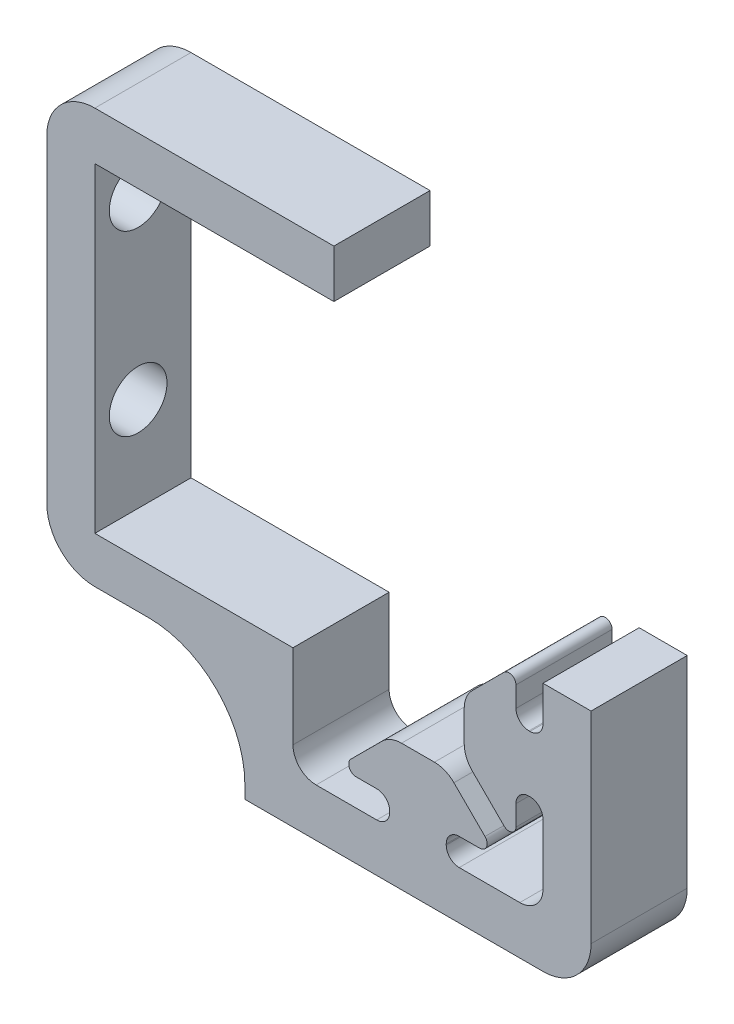
SolidWorks part; units mm, degrees
ref_plane "Front Plane" through (0, 0, 0) normal (0, 0, 1) x (1, 0, 0)
ref_plane "Top Plane" through (0, 0, 0) normal (0, 1, 0) x (1, 0, 0)
ref_plane "Right Plane" through (0, 0, 0) normal (1, 0, 0) x (0, 0, -1)
sketch "Sketch1" plane through (0, 0, 0) normal (0, 0, 1) x (1, 0, 0)
  line L0 (-10.5918, -13) -> (-4.3059, -13)
  line L1 (-4.3059, -13) -> (-4.2875, -13)
  line L2 (-2.9385, -11.651) -> (-2.9385, -11.5392)
  line L3 (-4.2875, -10.1902) -> (-6.4164, -10.1902)
  line L4 (-6.9677, -8.8575) -> (-3.7403, -5.636)
  line L5 (-1.7093, -4.7958) -> (1.7093, -4.7958)
  line L6 (3.7403, -5.636) -> (6.9677, -8.8575)
  line L7 (6.4164, -10.1902) -> (4.2875, -10.1902)
  line L8 (2.9385, -11.5392) -> (2.9385, -11.651)
  line L9 (4.2875, -13) -> (5.3216, -13)
  line L10 (5.3216, -13) -> (10.5918, -13)
  line L11 (13, -10.5918) -> (13, -5.3171)
  line L12 (13, -5.3171) -> (13, -4.2875)
  line L13 (11.651, -2.9385) -> (11.5392, -2.9385)
  line L14 (10.1902, -4.2875) -> (10.1902, -6.4021)
  line L15 (8.949, -6.917) -> (5.6529, -3.6284)
  line L16 (4.8085, -1.5932) -> (4.8085, 1.5932)
  line L17 (5.6529, 3.6284) -> (8.949, 6.917)
  line L18 (10.1902, 6.4021) -> (10.1902, 4.2875)
  line L19 (11.5392, 2.9385) -> (11.651, 2.9385)
  line L20 (13, 4.2875) -> (13, 5.3171)
  line L21 (13, 5.3171) -> (13, 10.5918) construction
  line L22 (10.5918, 13) -> (5.3216, 13) construction
  line L23 (5.3216, 13) -> (4.2875, 13) construction
  line L24 (2.9385, 11.651) -> (2.9385, 11.5392) construction
  line L25 (4.2875, 10.1902) -> (6.4768, 10.1902) construction
  line L26 (6.9951, 8.9367) -> (3.6864, 5.6355) construction
  line L27 (1.6558, 4.7958) -> (-1.6558, 4.7958) construction
  line L28 (-3.6864, 5.6355) -> (-6.9951, 8.9367) construction
  line L29 (-6.4768, 10.1902) -> (-4.2875, 10.1902) construction
  line L30 (-2.9385, 11.5392) -> (-2.9385, 11.651) construction
  line L31 (-4.2875, 13) -> (-4.3059, 13) construction
  line L32 (-4.3059, 13) -> (-10.5918, 13) construction
  line L33 (-13, 10.5918) -> (-13, 5.3171) construction
  line L34 (-13, 5.3171) -> (-13, 4.2875) construction
  line L35 (-11.651, 2.9385) -> (-11.5392, 2.9385) construction
  line L36 (-10.1902, 4.2875) -> (-10.1902, 6.4021) construction
  line L37 (-8.949, 6.917) -> (-5.6529, 3.6284) construction
  line L38 (-4.8085, 1.5932) -> (-4.8085, -1.5932) construction
  line L39 (-5.6529, -3.6284) -> (-8.949, -6.917) construction
  line L40 (-10.1902, -6.4021) -> (-10.1902, -4.2875) construction
  line L41 (-11.5392, -2.9385) -> (-11.651, -2.9385) construction
  line L42 (-13, -4.2875) -> (-13, -10.5918)
  line L44 (13, 5.3171) -> (13, 7.9544)
  line L45 (-33.4, 31.3527) -> (-13, 31.3527) construction
  line L46 (-33.4, 31.3527) -> (-33.4, -1.6473) construction
  line L47 (-33.4, -1.6473) -> (-13, -1.6473) construction
  line L48 (-13, 31.3527) -> (-13, -1.6473) construction
  line L49 (13, 7.9544) -> (18, 7.9544)
  line L50 (18, 7.9544) -> (18, -18)
  line L51 (18, -18) -> (-18, -18)
  line L52 (-18, -18) -> (-18, -6.6473)
  line L53 (-18, -6.6473) -> (-38.6, -6.6473)
  line L54 (-38.6, -6.6473) -> (-38.6, 36.4527)
  line L55 (-38.6, 36.4527) -> (-8.7453, 36.4527)
  line L56 (-8.7453, 36.4527) -> (-8.7453, 31.4527)
  line L57 (-8.7453, 31.4527) -> (-33.6, 31.4527)
  line L58 (-33.6, 31.4527) -> (-33.6, -1.8473)
  line L59 (-33.6, -1.8473) -> (-13, -1.8473)
  line L60 (-13, -1.8473) -> (-13, -4.2875)
  line L88 (-7.1797, -8.6452) -> (-3.9523, -5.4237) construction
  line L89 (-1.7093, -4.4958) -> (1.7093, -4.4958) construction
  line L90 (3.9523, -5.4237) -> (7.1797, -8.6452) construction
  line L91 (6.4164, -10.4902) -> (4.2875, -10.4902) construction
  line L92 (3.2385, -11.5392) -> (3.2385, -11.651) construction
  line L93 (4.2875, -12.7) -> (5.3216, -12.7) construction
  line L94 (5.3216, -12.7) -> (10.5918, -12.7) construction
  line L95 (12.7, -10.5918) -> (12.7, -5.3171) construction
  line L96 (12.7, -5.3171) -> (12.7, -4.2875) construction
  line L97 (11.651, -3.2385) -> (11.5392, -3.2385) construction
  line L98 (10.4902, -4.2875) -> (10.4902, -6.4021) construction
  line L99 (8.7371, -7.1294) -> (5.441, -3.8408) construction
  line L100 (4.5085, -1.5932) -> (4.5085, 1.5932) construction
  line L101 (5.441, 3.8408) -> (8.7371, 7.1294) construction
  line L102 (10.4902, 6.4021) -> (10.4902, 4.2875) construction
  line L103 (11.5392, 3.2385) -> (11.651, 3.2385) construction
  line L104 (12.7, 4.2875) -> (12.7, 5.3171) construction
  line L105 (12.7, 5.3171) -> (12.7, 10.5918) construction
  line L106 (10.5918, 12.7) -> (5.3216, 12.7) construction
  line L107 (5.3216, 12.7) -> (4.2875, 12.7) construction
  line L108 (3.2385, 11.651) -> (3.2385, 11.5392) construction
  line L109 (4.2875, 10.4902) -> (6.4768, 10.4902) construction
  line L110 (7.207, 8.7244) -> (3.8983, 5.4232) construction
  line L111 (1.6558, 4.4958) -> (-1.6558, 4.4958) construction
  line L112 (-3.8983, 5.4232) -> (-7.207, 8.7244) construction
  line L113 (-6.4768, 10.4902) -> (-4.2875, 10.4902) construction
  line L114 (-3.2385, 11.5392) -> (-3.2385, 11.651) construction
  line L115 (-4.2875, 12.7) -> (-4.3059, 12.7) construction
  line L116 (-4.3059, 12.7) -> (-10.5918, 12.7) construction
  line L117 (-12.7, 10.5918) -> (-12.7, 5.3171) construction
  line L118 (-12.7, 5.3171) -> (-12.7, 4.2875) construction
  line L119 (-11.651, 3.2385) -> (-11.5392, 3.2385) construction
  line L120 (-10.4902, 4.2875) -> (-10.4902, 6.4021) construction
  line L121 (-8.7371, 7.1294) -> (-5.441, 3.8408) construction
  line L122 (-4.5085, 1.5932) -> (-4.5085, -1.5932) construction
  line L123 (-5.441, -3.8408) -> (-8.7371, -7.1294) construction
  line L124 (-10.4902, -6.4021) -> (-10.4902, -4.2875) construction
  line L125 (-11.5392, -3.2385) -> (-11.651, -3.2385) construction
  line L126 (-12.7, -4.2875) -> (-12.7, -5.3171) construction
  line L127 (-12.7, -5.3171) -> (-12.7, -10.5918) construction
  line L128 (-10.5918, -12.7) -> (-4.3059, -12.7) construction
  line L129 (-4.3059, -12.7) -> (-4.2875, -12.7) construction
  line L130 (-3.2385, -11.651) -> (-3.2385, -11.5392) construction
  line L131 (-4.2875, -10.4902) -> (-6.4164, -10.4902) construction
  line L132 (-13, -4.2875) -> (-13, -5.3171) construction
  line L133 (-13, -5.3171) -> (-13, -10.5918) construction
  arc A0 (-4.2875, -13) -> (-2.9385, -11.651) centre (-4.2875, -11.651) ccw
  arc A2 (-2.9385, -11.5392) -> (-4.2875, -10.1902) centre (-4.2875, -11.5392) ccw
  arc A3 (-6.9677, -8.8575) -> (-6.4164, -10.1902) centre (-6.4164, -9.4098) ccw
  arc A4 (-1.7093, -4.7958) -> (-3.7403, -5.636) centre (-1.7093, -7.6708) ccw
  arc A5 (3.7403, -5.636) -> (1.7093, -4.7958) centre (1.7093, -7.6708) ccw
  arc A6 (6.4164, -10.1902) -> (6.9677, -8.8575) centre (6.4164, -9.4098) ccw
  arc A7 (4.2875, -10.1902) -> (2.9385, -11.5392) centre (4.2875, -11.5392) ccw
  arc A8 (2.9385, -11.651) -> (4.2875, -13) centre (4.2875, -11.651) ccw
  arc A9 (13, -4.2875) -> (11.651, -2.9385) centre (11.651, -4.2875) ccw
  arc A10 (11.5392, -2.9385) -> (10.1902, -4.2875) centre (11.5392, -4.2875) ccw
  arc A11 (8.949, -6.917) -> (10.1902, -6.4021) centre (9.4628, -6.4021) ccw
  arc A12 (4.8085, -1.5932) -> (5.6529, -3.6284) centre (7.6835, -1.5932) ccw
  arc A13 (5.6529, 3.6284) -> (4.8085, 1.5932) centre (7.6835, 1.5932) ccw
  arc A14 (10.1902, 6.4021) -> (8.949, 6.917) centre (9.4628, 6.4021) ccw
  arc A15 (10.1902, 4.2875) -> (11.5392, 2.9385) centre (11.5392, 4.2875) ccw
  arc A16 (11.651, 2.9385) -> (13, 4.2875) centre (11.651, 4.2875) ccw
  arc A17 (4.2875, 13) -> (2.9385, 11.651) centre (4.2875, 11.651) ccw construction
  arc A18 (2.9385, 11.5392) -> (4.2875, 10.1902) centre (4.2875, 11.5392) ccw construction
  arc A19 (6.9951, 8.9367) -> (6.4768, 10.1902) centre (6.4768, 9.4563) ccw construction
  arc A20 (1.6558, 4.7958) -> (3.6864, 5.6355) centre (1.6558, 7.6708) ccw construction
  arc A21 (-3.6864, 5.6355) -> (-1.6558, 4.7958) centre (-1.6558, 7.6708) ccw construction
  arc A22 (-6.4768, 10.1902) -> (-6.9951, 8.9367) centre (-6.4768, 9.4563) ccw construction
  arc A23 (-4.2875, 10.1902) -> (-2.9385, 11.5392) centre (-4.2875, 11.5392) ccw construction
  arc A24 (-2.9385, 11.651) -> (-4.2875, 13) centre (-4.2875, 11.651) ccw construction
  arc A25 (-13, 4.2875) -> (-11.651, 2.9385) centre (-11.651, 4.2875) ccw construction
  arc A26 (-11.5392, 2.9385) -> (-10.1902, 4.2875) centre (-11.5392, 4.2875) ccw construction
  arc A27 (-8.949, 6.917) -> (-10.1902, 6.4021) centre (-9.4628, 6.4021) ccw construction
  arc A28 (-4.8085, 1.5932) -> (-5.6529, 3.6284) centre (-7.6835, 1.5932) ccw construction
  arc A29 (-5.6529, -3.6284) -> (-4.8085, -1.5932) centre (-7.6835, -1.5932) ccw construction
  arc A30 (-10.1902, -6.4021) -> (-8.949, -6.917) centre (-9.4628, -6.4021) ccw construction
  arc A31 (-10.1902, -4.2875) -> (-11.5392, -2.9385) centre (-11.5392, -4.2875) ccw construction
  arc A32 (-11.651, -2.9385) -> (-13, -4.2875) centre (-11.651, -4.2875) ccw construction
  arc A33 (10.5918, -13) -> (13, -10.5918) centre (10.5918, -10.5918) ccw
  arc A34 (12.9998, 10.5628) -> (10.5628, 12.9998) centre (10.5918, 10.5918) ccw construction
  arc A35 (-10.5628, 12.9998) -> (-12.9998, 10.5628) centre (-10.5918, 10.5918) ccw construction
  arc A36 (-13, -10.5918) -> (-10.5918, -13) centre (-10.5918, -10.5918) ccw
  arc A37 (10.5628, -12.9998) -> (12.9998, -10.5628) centre (10.5918, -10.5918) ccw construction
  arc A38 (-12.9998, -10.5628) -> (-10.5918, -13) centre (-10.5918, -10.5918) ccw construction
  arc A104 (-7.1797, -8.6452) -> (-6.4164, -10.4902) centre (-6.4164, -9.4098) ccw construction
  arc A105 (-1.7093, -4.4958) -> (-3.9523, -5.4237) centre (-1.7093, -7.6708) ccw construction
  arc A106 (3.9523, -5.4237) -> (1.7093, -4.4958) centre (1.7093, -7.6708) ccw construction
  arc A107 (6.4164, -10.4902) -> (7.1797, -8.6452) centre (6.4164, -9.4098) ccw construction
  arc A108 (4.2875, -10.4902) -> (3.2385, -11.5392) centre (4.2875, -11.5392) ccw construction
  arc A109 (3.2385, -11.651) -> (4.2875, -12.7) centre (4.2875, -11.651) ccw construction
  arc A112 (10.5664, -12.6998) -> (12.6998, -10.5664) centre (10.5918, -10.5918) ccw construction
  arc A115 (12.7, -4.2875) -> (11.651, -3.2385) centre (11.651, -4.2875) ccw construction
  arc A116 (11.5392, -3.2385) -> (10.4902, -4.2875) centre (11.5392, -4.2875) ccw construction
  arc A117 (8.7371, -7.1294) -> (10.4902, -6.4021) centre (9.4628, -6.4021) ccw construction
  arc A118 (4.5085, -1.5932) -> (5.441, -3.8408) centre (7.6835, -1.5932) ccw construction
  arc A119 (5.441, 3.8408) -> (4.5085, 1.5932) centre (7.6835, 1.5932) ccw construction
  arc A120 (10.4902, 6.4021) -> (8.7371, 7.1294) centre (9.4628, 6.4021) ccw construction
  arc A121 (10.4902, 4.2875) -> (11.5392, 3.2385) centre (11.5392, 4.2875) ccw construction
  arc A122 (11.651, 3.2385) -> (12.7, 4.2875) centre (11.651, 4.2875) ccw construction
  arc A125 (12.6998, 10.5664) -> (10.5664, 12.6998) centre (10.5918, 10.5918) ccw construction
  arc A128 (4.2875, 12.7) -> (3.2385, 11.651) centre (4.2875, 11.651) ccw construction
  arc A129 (3.2385, 11.5392) -> (4.2875, 10.4902) centre (4.2875, 11.5392) ccw construction
  arc A130 (7.207, 8.7244) -> (6.4768, 10.4902) centre (6.4768, 9.4563) ccw construction
  arc A131 (1.6558, 4.4958) -> (3.8983, 5.4232) centre (1.6558, 7.6708) ccw construction
  arc A132 (-3.8983, 5.4232) -> (-1.6558, 4.4958) centre (-1.6558, 7.6708) ccw construction
  arc A133 (-6.4768, 10.4902) -> (-7.207, 8.7244) centre (-6.4768, 9.4563) ccw construction
  arc A134 (-4.2875, 10.4902) -> (-3.2385, 11.5392) centre (-4.2875, 11.5392) ccw construction
  arc A135 (-3.2385, 11.651) -> (-4.2875, 12.7) centre (-4.2875, 11.651) ccw construction
  arc A138 (-10.5664, 12.6998) -> (-12.6998, 10.5664) centre (-10.5918, 10.5918) ccw construction
  arc A141 (-12.7, 4.2875) -> (-11.651, 3.2385) centre (-11.651, 4.2875) ccw construction
  arc A142 (-11.5392, 3.2385) -> (-10.4902, 4.2875) centre (-11.5392, 4.2875) ccw construction
  arc A143 (-8.7371, 7.1294) -> (-10.4902, 6.4021) centre (-9.4628, 6.4021) ccw construction
  arc A144 (-4.5085, 1.5932) -> (-5.441, 3.8408) centre (-7.6835, 1.5932) ccw construction
  arc A145 (-5.441, -3.8408) -> (-4.5085, -1.5932) centre (-7.6835, -1.5932) ccw construction
  arc A146 (-10.4902, -6.4021) -> (-8.7371, -7.1294) centre (-9.4628, -6.4021) ccw construction
  arc A147 (-10.4902, -4.2875) -> (-11.5392, -3.2385) centre (-11.5392, -4.2875) ccw construction
  arc A148 (-11.651, -3.2385) -> (-12.7, -4.2875) centre (-11.651, -4.2875) ccw construction
  arc A151 (-12.6998, -10.5664) -> (-10.5918, -12.7) centre (-10.5918, -10.5918) ccw construction
  arc A154 (-4.2875, -12.7) -> (-3.2385, -11.651) centre (-4.2875, -11.651) ccw construction
  arc A155 (-3.2385, -11.5392) -> (-4.2875, -10.4902) centre (-4.2875, -11.5392) ccw construction
  dimension "D2" = 33
  dimension "D3" = 20.4
  dimension "D5" = 11.3527
  dimension "D6" = 5
  dimension "D7" = 5
  dimension "D9" = 5
  dimension "D10" = 5
  dimension "D11" = 5
  dimension "D12" = 0.2
  dimension "D13" = 0.2
  dimension ".2" = 0.2
  dimension "D1" = 0.3
extrude "Boss-Extrude1" add sketch "Sketch1" along normal blind 10 contours A36 L42 L60 L59 L58 L57 L56 L55 L54 L53 L52 L51 L50 L49 L44 L20 A16 L19 A15 L18 A14 L17 A13 L16 A12 L15 A11 L14 A10 L13 A9 L12 L11 A33 L10 L9 A8 L8 A7 L7 A6 L6 A5 L5 A4 L4 A3 L3 A2 L2 A0
sketch "Sketch2" plane through (-38.6, 0, 0) normal (-1, 0, 0) x (0, 0, 1)
  line L0 (0, -6.6473) -> (0, 36.4527) construction
  line L3 (4.5, 29.4527) -> (4.5, 26.4527) construction
  line L4 (10, 31.4527) -> (0, 31.4527) construction
  line L5 (4.5, 10.9527) -> (4.5, 4.9527) construction
  line L6 (4.5, 26.4527) -> (4.5, 23.4527) construction
  circle A0 centre (4.5, 26.4527) radius 3
  circle A1 centre (4.5, 7.9527) radius 3
  dimension "D1" = 6
  dimension "D3" = 6
  dimension "D2" = 5
  dimension "D4" = 12.5
  dimension "D5" = 4.5
extrude "Cut-Extrude1" cut sketch "Sketch2" against normal up to next
fillet "Fillet1" radius 10 1 edges at (-18, -6.6473, 5)
fillet "Fillet2" radius 5 3 edges at (18, -18, 5) (-38.6, -6.6473, 5) (-38.6, 36.4527, 5)
mirror "Mirror1" about plane through (0, 0, 0) normal (0, 0, 1) of bodies 102
sketch "Sketch3" plane through (-38.6, 0, 0) normal (-1, 0, 0) x (0, 0, 1)
  line L0 (0, 36.4527) -> (0, 49.9999)
  line L1 (0, 49.9999) -> (29.852, 49.9999)
  line L2 (29.852, 49.9999) -> (29.852, -34.6676)
  line L3 (29.852, -34.6676) -> (0, -34.6676)
  line L4 (0, -34.6676) -> (0, 36.4527)
extrude "Cut-Extrude2" cut sketch "Sketch3" against normal blind 125
